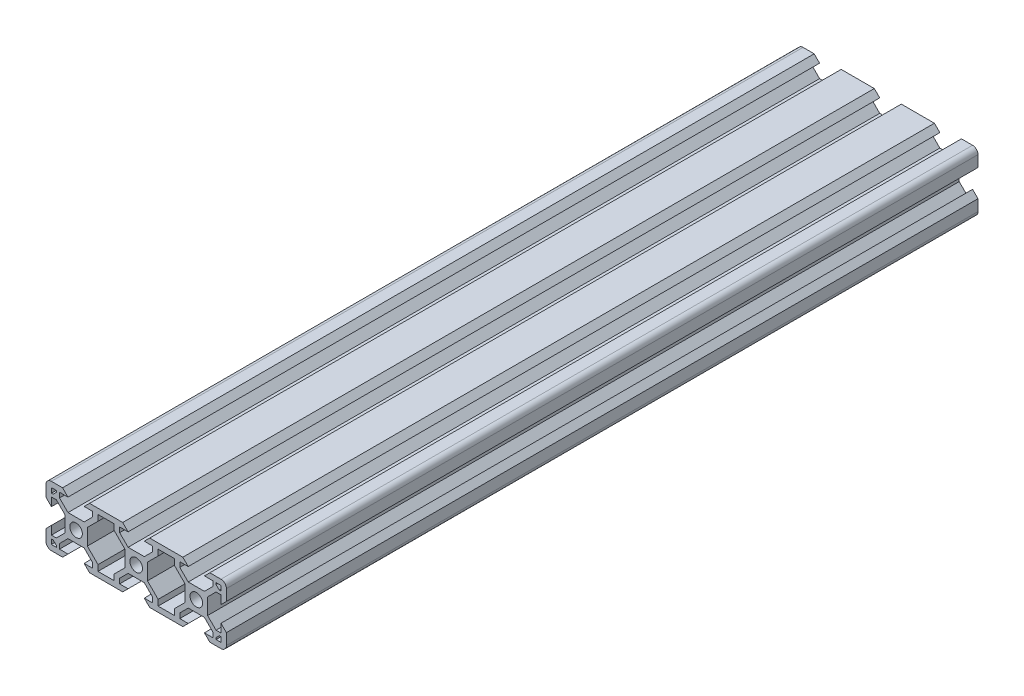
SolidWorks part; units mm, degrees
material "5052-H38, Barre (SS)"
ref_plane "Plan de face" through (0, 0, 0) normal (0, 0, 1) x (1, 0, 0)
ref_plane "Plan de dessus" through (0, 0, 0) normal (0, 1, 0) x (1, 0, 0)
ref_plane "Plan de droite" through (0, 0, 0) normal (1, 0, 0) x (0, 0, -1)
sketch "Esquisse1" plane through (0, 0, 0) normal (0, 0, 1) x (1, 0, 0)
  line L0 (0, 0) -> (-30, 0) construction
  line L1 (0, 0) -> (0, 10) construction
  line L2 (-20, 0) -> (-30, 10) construction
  line L3 (-20, 3.7507) -> (-22.69, 3.7507)
  line L4 (-22.69, 3.7507) -> (-25.4993, 6.56)
  line L5 (-25.4993, 6.56) -> (-25.4993, 8.2)
  line L6 (-25.4993, 8.2) -> (-22.69, 8.2)
  line L7 (-22.69, 8.2) -> (-24.49, 10)
  line L8 (-24.49, 10) -> (-28.2, 10)
  line L9 (-20, 0) -> (-20, 10) construction
  line L10 (-30, 4.49) -> (-30, 8.2)
  line L11 (-28.2, 2.69) -> (-30, 4.49)
  line L12 (-28.2, 5.4993) -> (-28.2, 2.69)
  line L13 (-26.56, 5.4993) -> (-28.2, 5.4993)
  line L14 (-23.7507, 2.69) -> (-26.56, 5.4993)
  line L15 (-23.7507, 0) -> (-23.7507, 2.69)
  line L16 (-28.2, 8.2) -> (-28.2, 6.5693)
  line L17 (-28.2, 6.5693) -> (-27.63, 6.5693)
  line L18 (-27.63, 6.5693) -> (-26.5693, 7.63)
  line L19 (-26.5693, 7.63) -> (-26.5693, 8.2)
  line L20 (-26.5693, 8.2) -> (-28.2, 8.2)
  line L21 (-23.7507, 0) -> (-23.7507, -2.69)
  line L22 (-23.7507, -2.69) -> (-26.56, -5.4993)
  line L23 (-26.56, -5.4993) -> (-28.2, -5.4993)
  line L24 (-28.2, -5.4993) -> (-28.2, -2.69)
  line L25 (-28.2, -2.69) -> (-30, -4.49)
  line L26 (-30, -4.49) -> (-30, -8.2)
  line L27 (-24.49, -10) -> (-28.2, -10)
  line L28 (-22.69, -8.2) -> (-24.49, -10)
  line L29 (-25.4993, -8.2) -> (-22.69, -8.2)
  line L30 (-25.4993, -6.56) -> (-25.4993, -8.2)
  line L31 (-22.69, -3.7507) -> (-25.4993, -6.56)
  line L32 (-20, -3.7507) -> (-22.69, -3.7507)
  line L33 (-26.5693, -7.63) -> (-27.63, -6.5693)
  line L34 (-27.63, -6.5693) -> (-28.2, -6.5693)
  line L35 (-28.2, -6.5693) -> (-28.2, -8.2)
  line L36 (-28.2, -8.2) -> (-26.5693, -8.2)
  line L37 (-26.5693, -8.2) -> (-26.5693, -7.63)
  line L38 (-2.69, -8.2) -> (-4.49, -10)
  line L39 (-2.69, 8.2) -> (-4.49, 10)
  line L40 (-7.3007, -8.2) -> (-7.3007, -6.24)
  line L41 (-7.3007, -6.24) -> (-3.7507, -2.69)
  line L42 (-3.7507, 2.69) -> (-3.7507, -2.69)
  line L43 (-7.3007, 6.24) -> (-3.7507, 2.69)
  line L44 (-7.3007, 8.2) -> (-7.3007, 6.24)
  line L45 (26.5693, 8.2) -> (28.2, 8.2)
  line L46 (26.5693, 7.63) -> (26.5693, 8.2)
  line L47 (27.63, 6.5693) -> (26.5693, 7.63)
  line L48 (28.2, 6.5693) -> (27.63, 6.5693)
  line L49 (28.2, 8.2) -> (28.2, 6.5693)
  line L50 (26.5693, -8.2) -> (26.5693, -7.63)
  line L51 (28.2, -8.2) -> (26.5693, -8.2)
  line L52 (28.2, -6.5693) -> (28.2, -8.2)
  line L53 (27.63, -6.5693) -> (28.2, -6.5693)
  line L54 (26.5693, -7.63) -> (27.63, -6.5693)
  line L55 (7.3007, 8.2) -> (7.3007, 6.24)
  line L56 (7.3007, 8.2) -> (12.6993, 8.2)
  line L57 (12.6993, 8.2) -> (12.6993, 6.24)
  line L58 (12.6993, 6.24) -> (16.2493, 2.69)
  line L59 (16.2493, 2.69) -> (16.2493, -2.69)
  line L60 (12.6993, -6.24) -> (16.2493, -2.69)
  line L61 (12.6993, -8.2) -> (12.6993, -6.24)
  line L62 (7.3007, -8.2) -> (12.6993, -8.2)
  line L63 (7.3007, -8.2) -> (7.3007, -6.24)
  line L64 (7.3007, -6.24) -> (3.7507, -2.69)
  line L65 (3.7507, 2.69) -> (3.7507, -2.69)
  line L66 (7.3007, 6.24) -> (3.7507, 2.69)
  line L67 (2.69, -8.2) -> (4.49, -10)
  line L68 (15.51, -10) -> (4.49, -10)
  line L69 (17.31, -8.2) -> (15.51, -10)
  line L70 (14.5007, -8.2) -> (17.31, -8.2)
  line L71 (14.5007, -6.56) -> (14.5007, -8.2)
  line L72 (17.31, -3.7507) -> (14.5007, -6.56)
  line L73 (20, -3.7507) -> (17.31, -3.7507)
  line L74 (20, -3.7507) -> (22.69, -3.7507)
  line L75 (22.69, -3.7507) -> (25.4993, -6.56)
  line L76 (25.4993, -6.56) -> (25.4993, -8.2)
  line L77 (25.4993, -8.2) -> (22.69, -8.2)
  line L78 (22.69, -8.2) -> (24.49, -10)
  line L79 (24.49, -10) -> (28.2, -10)
  line L80 (30, -4.49) -> (30, -8.2)
  line L81 (28.2, -2.69) -> (30, -4.49)
  line L82 (28.2, -5.4993) -> (28.2, -2.69)
  line L83 (26.56, -5.4993) -> (28.2, -5.4993)
  line L84 (0, 0) -> (-10, 10) construction
  line L85 (-17.31, 3.7507) -> (-14.5007, 6.56)
  line L86 (-14.5007, 6.56) -> (-14.5007, 8.2)
  line L87 (-14.5007, 8.2) -> (-17.31, 8.2)
  line L88 (-17.31, 8.2) -> (-15.51, 10)
  line L89 (-20, 3.7507) -> (-17.31, 3.7507)
  line L90 (-20, -3.7507) -> (-17.31, -3.7507)
  line L91 (-17.31, -3.7507) -> (-14.5007, -6.56)
  line L92 (-14.5007, -6.56) -> (-14.5007, -8.2)
  line L93 (-14.5007, -8.2) -> (-17.31, -8.2)
  line L94 (-17.31, -8.2) -> (-15.51, -10)
  line L95 (-10, 10) -> (-10, 0) construction
  line L96 (-15.51, 10) -> (-4.49, 10)
  line L97 (-15.51, -10) -> (-4.49, -10)
  line L98 (-7.3007, 8.2) -> (-12.6993, 8.2)
  line L99 (-12.6993, 8.2) -> (-12.6993, 6.24)
  line L100 (-12.6993, 6.24) -> (-16.2493, 2.69)
  line L101 (-16.2493, 2.69) -> (-16.2493, -2.69)
  line L102 (-20, 0) -> (-10, 10) construction
  line L103 (-17.31, 3.7507) -> (-16.2493, 2.69) construction
  line L104 (-12.6993, -6.24) -> (-16.2493, -2.69)
  line L105 (-12.6993, -8.2) -> (-12.6993, -6.24)
  line L106 (-7.3007, -8.2) -> (-12.6993, -8.2)
  line L107 (23.7507, -2.69) -> (26.56, -5.4993)
  line L108 (23.7507, 0) -> (23.7507, -2.69)
  line L109 (23.7507, 0) -> (23.7507, 2.69)
  line L110 (23.7507, 2.69) -> (26.56, 5.4993)
  line L111 (26.56, 5.4993) -> (28.2, 5.4993)
  line L112 (28.2, 5.4993) -> (28.2, 2.69)
  line L113 (28.2, 2.69) -> (30, 4.49)
  line L114 (30, 4.49) -> (30, 8.2)
  line L115 (24.49, 10) -> (28.2, 10)
  line L116 (22.69, 8.2) -> (24.49, 10)
  line L117 (25.4993, 8.2) -> (22.69, 8.2)
  line L118 (25.4993, 6.56) -> (25.4993, 8.2)
  line L119 (22.69, 3.7507) -> (25.4993, 6.56)
  line L120 (20, 3.7507) -> (22.69, 3.7507)
  line L121 (20, 3.7507) -> (17.31, 3.7507)
  line L122 (17.31, 3.7507) -> (14.5007, 6.56)
  line L123 (14.5007, 6.56) -> (14.5007, 8.2)
  line L124 (14.5007, 8.2) -> (17.31, 8.2)
  line L125 (17.31, 8.2) -> (15.51, 10)
  line L126 (15.51, 10) -> (4.49, 10)
  line L127 (2.69, 8.2) -> (4.49, 10)
  line L128 (-2.69, 8.2) -> (-5.4993, 8.2)
  line L129 (-5.4993, 8.2) -> (-5.4993, 6.56)
  line L130 (-5.4993, 6.56) -> (-2.69, 3.7507)
  line L131 (-2.69, 3.7507) -> (2.69, 3.7507)
  line L132 (5.4993, 6.56) -> (2.69, 3.7507)
  line L133 (5.4993, 8.2) -> (5.4993, 6.56)
  line L134 (5.4993, 8.2) -> (2.69, 8.2)
  line L135 (2.69, 8.2) -> (5.4993, 8.2)
  line L136 (5.4993, -8.2) -> (2.69, -8.2)
  line L137 (5.4993, -8.2) -> (5.4993, -6.56)
  line L138 (5.4993, -6.56) -> (2.69, -3.7507)
  line L139 (-2.69, -3.7507) -> (2.69, -3.7507)
  line L140 (-5.4993, -6.56) -> (-2.69, -3.7507)
  line L141 (-5.4993, -8.2) -> (-5.4993, -6.56)
  line L142 (-2.69, -8.2) -> (-5.4993, -8.2)
  circle A0 centre (0, 0) radius 2.1
  circle A1 centre (-20, 0) radius 2.1
  arc A2 (-28.2, 10) -> (-30, 8.2) centre (-28.2, 8.2) ccw
  arc A3 (-30, -8.2) -> (-28.2, -10) centre (-28.2, -8.2) ccw
  circle A4 centre (20, 0) radius 2.1
  arc A5 (30, -8.2) -> (28.2, -10) centre (28.2, -8.2) cw
  arc A6 (28.2, 10) -> (30, 8.2) centre (28.2, 8.2) cw
  point P26 (-27.0997, 7.0997)
  point P32 (-10, -10)
  point P55 (-10, -8.2)
  point P61 (-10, 8.2)
  point P106 (-16.7797, 3.2203)
  point P108 (-16.2493, 0)
  point P153 (0, 3.7507)
  point P154 (0, 3.7507)
  dimension "D3" = 4.2
  dimension "D1" = 30
  dimension "D2" = 10
  dimension "D5" = 20
  dimension "D6" = 1.5
  dimension "D7" = 1.64
  dimension "D8" = 1.8
  dimension "D9" = 5.38
  dimension "D10" = 1.07
  dimension "D12" = 45
  dimension "D15" = 1.96
  dimension "D4" = 2
  dimension "D11" = 2
  dimension "D13" = 2
  dimension "D14" = 2
extrude "Boss.-Extru.1" add sketch "Esquisse1" along normal mid plane 250 contours A6 L115 L116 L117 L118 L119 L120 L121 L122 L123 L124 L125 L126 L127 L134 L133 L132 L131 L130 L129 L128 L39 L96 L88 L87 L86 L85 L89 L3 L4 L5 L6 L7 L8 A2 L10 L11 L12 L13 L14 L15 L21 L22 L23 L24 L25 L26 A3 L27 L28 L29
